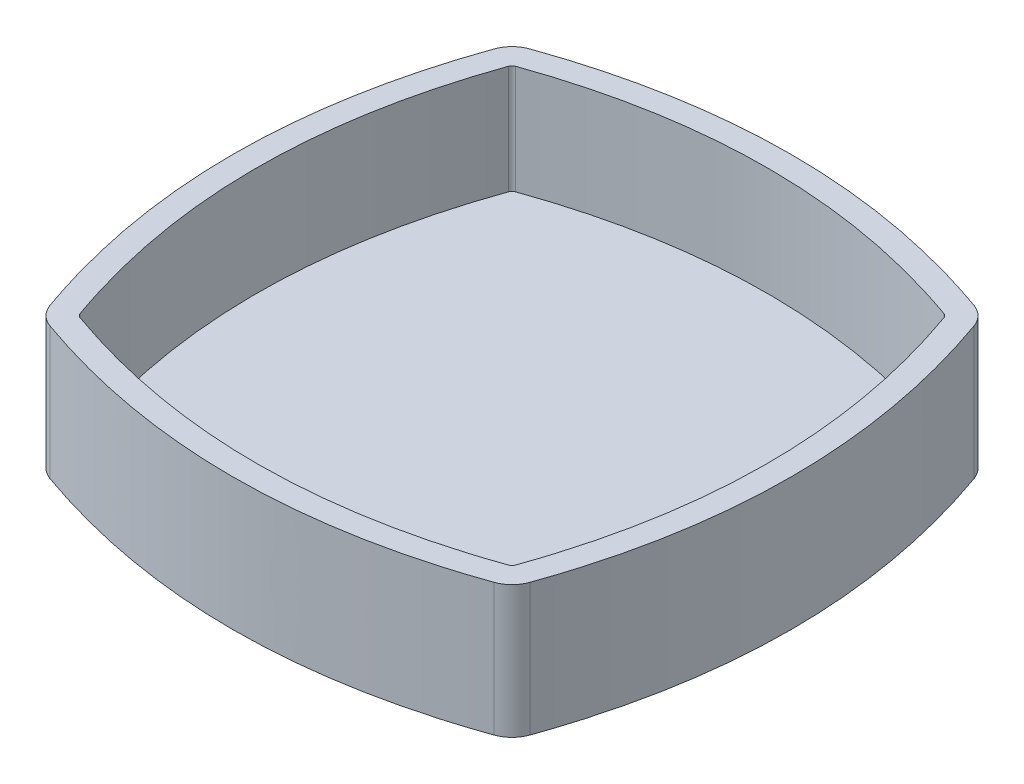
SolidWorks part; units mm, degrees
ref_plane "Front Plane" through (0, 0, 0) normal (0, 0, 1) x (1, 0, 0)
ref_plane "Top Plane" through (0, 0, 0) normal (0, 1, 0) x (1, 0, 0)
ref_plane "Right Plane" through (0, 0, 0) normal (1, 0, 0) x (0, 0, -1)
sketch "Sketch1" plane through (0, 0, 0) normal (0, 1, 0) x (1, 0, 0)
  line L0 (-30.1625, 0) -> (30.1625, 0)
  line L9 (-25.4, -25.4) -> (25.4, 25.4) construction
  line L10 (-25.4, 25.4) -> (25.4, -25.4) construction
  line L11 (0, 0) -> (-37.7304, 0) construction
  line L12 (-37.7304, 0) -> (0, 0) construction
  line L13 (0, 0) -> (0, 28.6183) construction
  line L14 (0, -30.1625) -> (0, 30.1625)
  spline S0 degree 2 poles (-25.4, 25.4) (-34.925, 0) (-25.4, -25.4) knots 0 0 0 1 1 1
  spline S1 degree 2 poles (-25.4, 25.4) (0, 34.925) (25.4, 25.4) knots 0 0 0 1 1 1
  spline S2 degree 2 poles (-25.4, -25.4) (0, -34.925) (25.4, -25.4) knots 0 0 0 1 1 1
  spline S3 degree 2 poles (25.4, 25.4) (34.925, 0) (25.4, -25.4) knots 0 0 0 1 1 1
  point P0 (0, 0)
  dimension "D1" = 50.8
  dimension "D2" = 50.8
  dimension "D3" = 30.1625
  dimension "D4" = 30.1625
extrude "Boss-Extrude1" add sketch "Sketch1" along normal blind 14.2875 contours S0 S2 L14 L0 | S1 S0 L0 L14 | S3 S1 L14 L0 | S3 L0 L14 S2
fillet "Fillet1" radius 3.175 4 edges at (-25.4, 7.1437, -25.4) (25.4, 7.1437, -25.4) (-25.4, 7.1437, 25.4) (25.4, 7.1437, 25.4)
shell "Shell1" thickness 2.54
